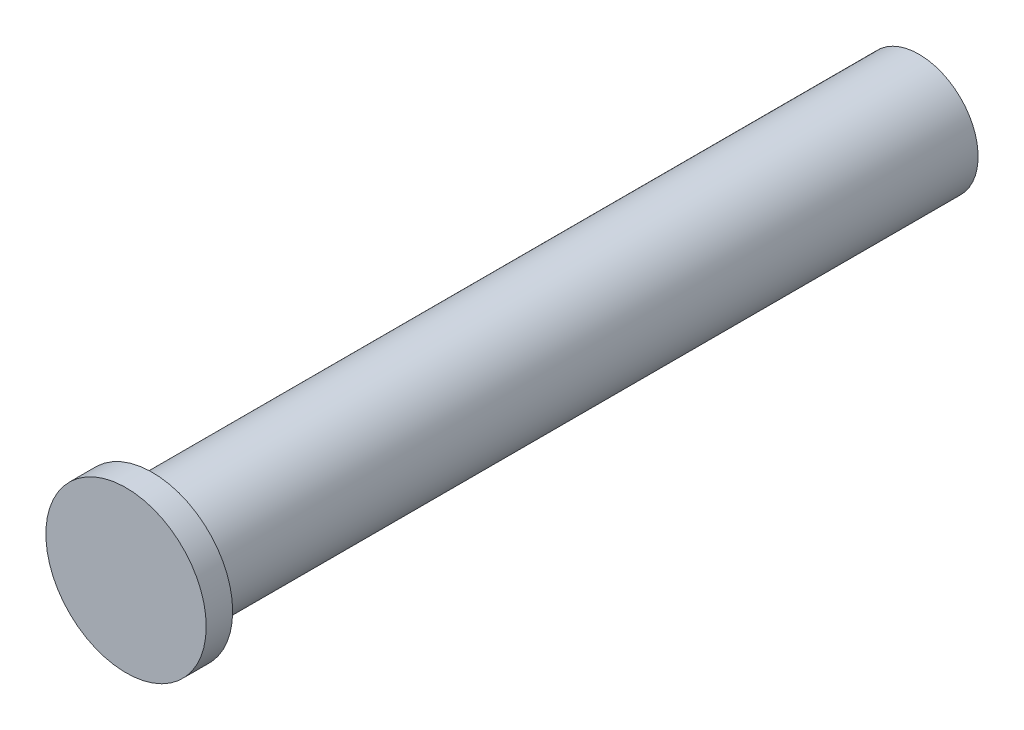
SolidWorks part; units mm, degrees
ref_plane "Plano frontal" through (0, 0, 0) normal (0, 0, 1) x (1, 0, 0)
ref_plane "Plano superior" through (0, 0, 0) normal (0, 1, 0) x (1, 0, 0)
ref_plane "Plano direito" through (0, 0, 0) normal (1, 0, 0) x (0, 0, -1)
sketch "Esboço1" plane through (0, 0, 0) normal (0, 0, 1) x (1, 0, 0)
  circle A0 centre (0, 0) radius 9.1
  dimension "D1" = 18.2
extrude "Ressalto-extrusão1" add sketch "Esboço1" against normal blind 3
sketch "Esboço2" plane through (0, 0, -3) normal (0, 0, -1) x (-1, 0, 0)
  circle A0 centre (0, 0) radius 6.7
  dimension "D1" = 13.4
extrude "Ressalto-extrusão2" add sketch "Esboço2" along normal blind 87
hole_wizard "Furo roscado para conduíte de M4x0.72" positions "Esboço5" profile "Esboço6" tap size "M4x0.7" standard "Helicoil® Metric"
sketch "Esboço5" plane through (0, 0, -90) normal (0, 0, -1) x (-1, 0, 0)
  point P0 (0, 0)
sketch "Esboço6" plane through (0, 0, -90) normal (1, 0, 0) x (0, 1, 0)
  line L0 (0, 0) -> (0, 23.2618)
  line L1 (0, 23.2618) -> (2.1, 22)
  line L2 (2.1, 22) -> (2.1, 0)
  line L5 (2.1, 0) -> (0, 0)
  line L10 (0, 23.2618) -> (-2.1, 22) construction
  line L11 (0, -6.35) -> (0, 107.95) construction
  dimension "Tap Drill Dia." = 4.2
  dimension "Tap Drill Depth" = 22
  dimension "Drill Angle" = 118
cosmetic thread "Rosca de furo2" parameters "D1"=22, "D2"=5.007
